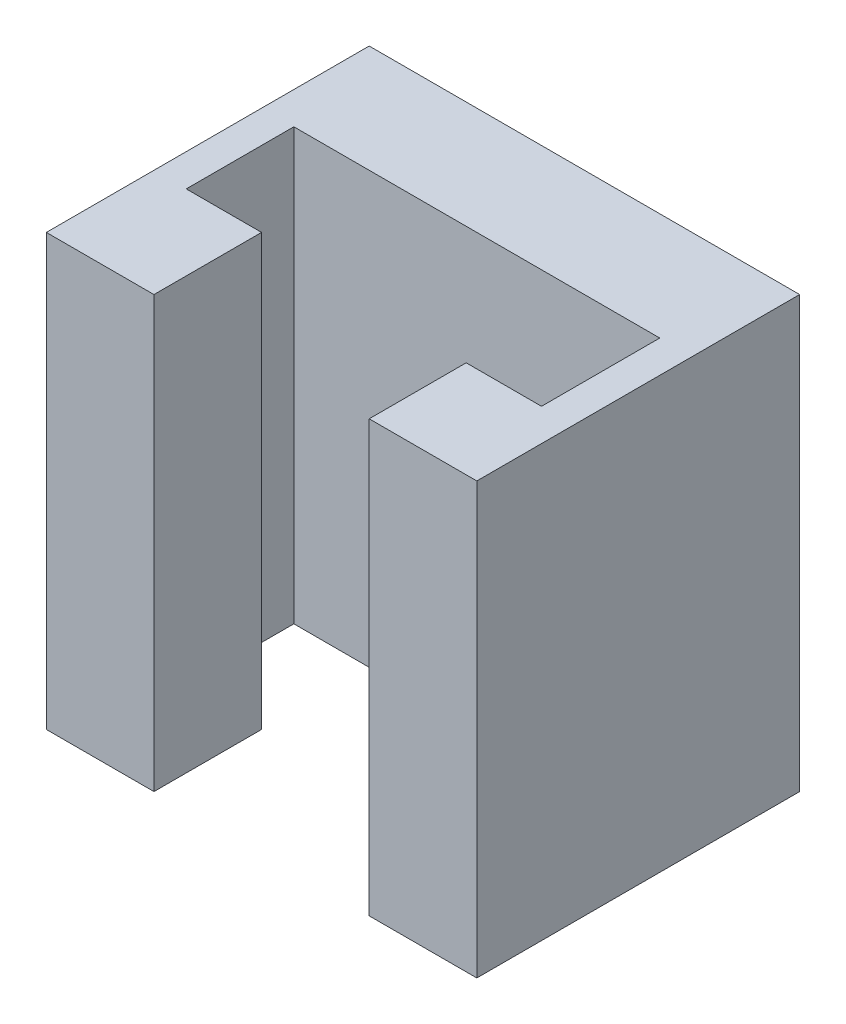
SolidWorks part; units mm, degrees
ref_plane "前视基准面" through (0, 0, 0) normal (0, 0, 1) x (1, 0, 0)
ref_plane "上视基准面" through (0, 0, 0) normal (0, 1, 0) x (1, 0, 0)
ref_plane "右视基准面" through (0, 0, 0) normal (1, 0, 0) x (0, 0, -1)
other "Configuration Table"
sketch "草图4" plane through (0, 0, 0) normal (0, 1, 0) x (1, 0, 0)
  line L8 (0, 0) -> (5, 0)
  line L9 (5, 0) -> (5, 5)
  line L10 (5, 5) -> (1.5, 5)
  line L11 (1.5, 5) -> (1.5, 10)
  line L12 (1.5, 10) -> (18.5, 10)
  line L13 (18.5, 10) -> (18.5, 4.5062)
  line L14 (18.5, 4.5062) -> (15, 4.5062)
  line L15 (15, 4.5062) -> (15, 0)
  line L16 (15, 0) -> (20, 0)
  line L17 (20, 0) -> (20, 15)
  line L18 (20, 15) -> (0, 15)
  line L19 (0, 15) -> (0, 0)
  point P2 (18.5, 7.2531)
  dimension "D1" = 10
  dimension "D2" = 1.5
  dimension "D3" = 5
  dimension "D4" = 5
  dimension "D5" = 5
  dimension "D6" = 15
  dimension "D7" = 5
  dimension "D8" = 5
  dimension "D9" = 1.5
extrude "凸台-拉伸1" add sketch "草图4" along normal blind 20
